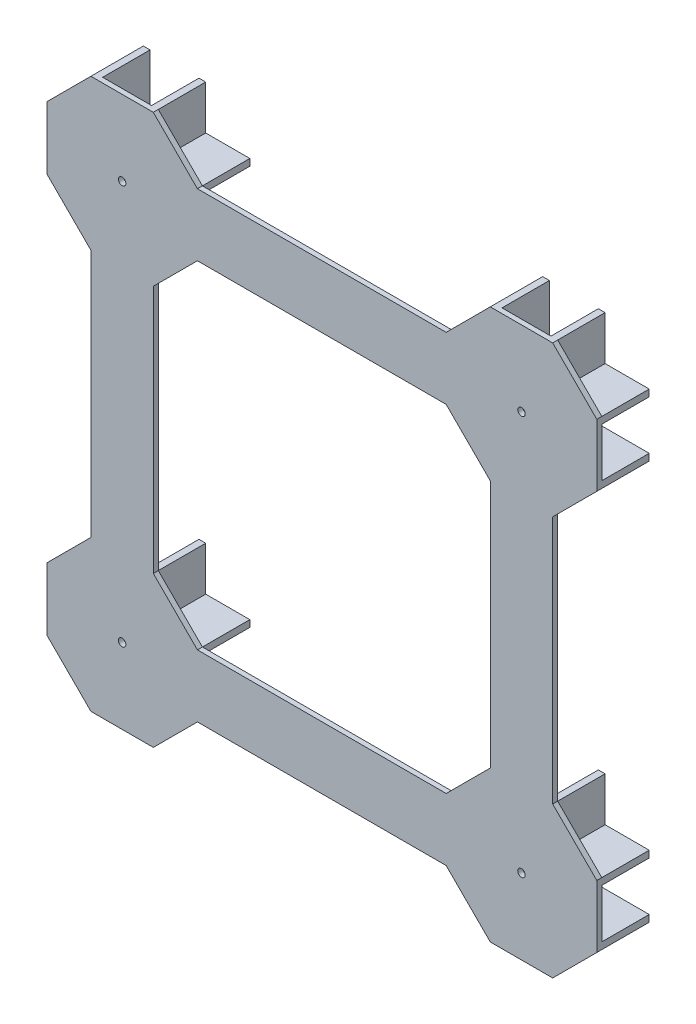
SolidWorks part; units mm, degrees
ref_plane "Front Plane" through (0, 0, 0) normal (0, 0, 1) x (1, 0, 0)
ref_plane "Top Plane" through (0, 0, 0) normal (0, 1, 0) x (1, 0, 0)
ref_plane "Right Plane" through (0, 0, 0) normal (1, 0, 0) x (0, 0, -1)
sketch "Sketch1" plane through (0, 0, 0) normal (0, 0, 1) x (1, 0, 0)
  line L0 (12.5, -110.1777) -> (-12.5, -110.1777)
  line L1 (-12.5, -110.1777) -> (-30.1777, -92.5)
  line L3 (-30.1777, -67.5) -> (-12.5, -49.8223)
  line L5 (12.5, -49.8223) -> (30.1777, -67.5)
  line L6 (30.1777, -67.5) -> (30.1777, -92.5)
  line L7 (30.1777, -92.5) -> (12.5, -110.1777)
  line L8 (9.5, 250) -> (9.5, -250) construction
  line L9 (-9.5, 250) -> (-9.5, -250) construction
  line L10 (9.5, -89.5) -> (170, -89.5) construction
  line L11 (-147.5, -110.1777) -> (-172.5, -110.1777)
  line L12 (-172.5, -110.1777) -> (-190.1777, -92.5)
  line L13 (-190.1777, -92.5) -> (-190.1777, -67.5)
  line L14 (-190.1777, -67.5) -> (-172.5, -49.8223)
  line L16 (-147.5, -49.8223) -> (-129.8223, -67.5)
  line L18 (-129.8223, -92.5) -> (-147.5, -110.1777)
  line L20 (-172.5, 49.8223) -> (-190.1777, 67.5)
  line L21 (-190.1777, 67.5) -> (-190.1777, 92.5)
  line L22 (-190.1777, 92.5) -> (-172.5, 110.1777)
  line L23 (-172.5, 110.1777) -> (-147.5, 110.1777)
  line L24 (-147.5, 110.1777) -> (-129.8223, 92.5)
  line L25 (-129.8223, 92.5) -> (-129.8223, 67.5) construction
  line L26 (-129.8223, 67.5) -> (-147.5, 49.8223)
  line L27 (12.5, 49.8223) -> (-12.5, 49.8223)
  line L28 (-12.5, 49.8223) -> (-30.1777, 67.5)
  line L30 (-30.1777, 92.5) -> (-12.5, 110.1777)
  line L31 (-12.5, 110.1777) -> (12.5, 110.1777)
  line L32 (12.5, 110.1777) -> (30.1777, 92.5)
  line L33 (30.1777, 92.5) -> (30.1777, 67.5)
  line L34 (30.1777, 67.5) -> (12.5, 49.8223)
  line L37 (-172.5, 49.8223) -> (-172.5, -49.8223)
  line L39 (-147.5, 49.8223) -> (-147.5, -49.8223)
  line L40 (-12.5, 49.8223) -> (12.5, 49.8223)
  line L41 (-12.5, 49.8223) -> (-12.5, -49.8223)
  line L43 (12.5, 49.8223) -> (12.5, -49.8223)
  line L44 (-30.1777, -67.5) -> (-129.8223, -67.5)
  line L46 (-30.1777, -92.5) -> (-129.8223, -92.5)
  line L48 (-129.8223, 67.5) -> (-30.1777, 67.5)
  line L49 (-129.8223, 67.5) -> (-129.8223, 92.5) construction
  line L50 (-129.8223, 92.5) -> (-30.1777, 92.5)
  line L54 (-129.8223, -67.5) -> (-129.8223, -92.5) [skipped]
  line L55 (-147.5, 49.8223) -> (-172.5, 49.8223) [skipped]
  dimension "D1" = 3
  dimension "D2" = 3
  dimension "D3" = 135
  dimension "D4" = 3
  dimension "D5" = 2
  dimension "D6" = 2
extrude "Boss-Extrude1" add sketch "Sketch1" along normal blind 2
sketch "Sketch2" plane through (0, 0, 0) normal (0, 0, -1) x (-1, 0, 0)
  line L0 (30.1777, -67.5) -> (12.5, -67.5)
  line L1 (12.5, -67.5) -> (12.5, -49.8223)
  line L2 (12.5, -49.8223) -> (9.8, -49.8223)
  line L4 (9.8, -49.8223) -> (9.8, -70.2)
  line L5 (9.8, -70.2) -> (30.1777, -70.2)
  line L7 (30.1777, -70.2) -> (30.1777, -67.5)
  line L8 (9.5, 250) -> (9.5, -250) construction
  line L9 (12.5, -92.5) -> (30.1777, -92.5)
  line L10 (30.1777, -92.5) -> (30.1777, -89.8)
  line L11 (30.1777, -89.8) -> (9.8, -89.8)
  line L12 (12.5, -110.1777) -> (12.5, -92.5)
  line L13 (9.8, -110.1777) -> (12.5, -110.1777)
  line L14 (9.8, -89.8) -> (9.8, -110.1777)
  line L15 (-12.5, -92.5) -> (-12.5, -110.1777)
  line L16 (-12.5, -110.1777) -> (-9.8, -110.1777)
  line L17 (-9.8, -110.1777) -> (-9.8, -89.8)
  line L18 (-30.1777, -92.5) -> (-12.5, -92.5)
  line L19 (-30.1777, -89.8) -> (-30.1777, -92.5)
  line L20 (-9.8, -89.8) -> (-30.1777, -89.8)
  line L21 (-12.5, -67.5) -> (-30.1777, -67.5)
  line L22 (-30.1777, -67.5) -> (-30.1777, -70.2)
  line L23 (-30.1777, -70.2) -> (-9.8, -70.2)
  line L24 (-12.5, -49.8223) -> (-12.5, -67.5)
  line L25 (-9.8, -49.8223) -> (-12.5, -49.8223)
  line L26 (-9.8, -70.2) -> (-9.8, -49.8223)
  line L27 (190.1777, -67.5) -> (172.5, -67.5)
  line L28 (172.5, -67.5) -> (172.5, -49.8223)
  line L29 (172.5, -49.8223) -> (169.8, -49.8223)
  line L30 (169.8, -49.8223) -> (169.8, -70.2)
  line L31 (169.8, -70.2) -> (190.1777, -70.2)
  line L32 (190.1777, -70.2) -> (190.1777, -67.5)
  line L33 (172.5, -92.5) -> (190.1777, -92.5)
  line L34 (190.1777, -92.5) -> (190.1777, -89.8)
  line L35 (190.1777, -89.8) -> (169.8, -89.8)
  line L36 (172.5, -110.1777) -> (172.5, -92.5)
  line L37 (169.8, -110.1777) -> (172.5, -110.1777)
  line L38 (169.8, -89.8) -> (169.8, -110.1777)
  line L39 (147.5, -92.5) -> (147.5, -110.1777)
  line L40 (147.5, -110.1777) -> (150.2, -110.1777)
  line L41 (150.2, -110.1777) -> (150.2, -89.8)
  line L42 (129.8223, -92.5) -> (147.5, -92.5)
  line L43 (129.8223, -89.8) -> (129.8223, -92.5)
  line L44 (150.2, -89.8) -> (129.8223, -89.8)
  line L45 (147.5, -67.5) -> (129.8223, -67.5)
  line L46 (129.8223, -67.5) -> (129.8223, -70.2)
  line L47 (129.8223, -70.2) -> (150.2, -70.2)
  line L48 (147.5, -49.8223) -> (147.5, -67.5)
  line L49 (150.2, -49.8223) -> (147.5, -49.8223)
  line L50 (150.2, -70.2) -> (150.2, -49.8223)
  line L51 (190.1777, 92.5) -> (172.5, 92.5)
  line L52 (172.5, 92.5) -> (172.5, 110.1777)
  line L53 (172.5, 110.1777) -> (169.8, 110.1777)
  line L54 (169.8, 110.1777) -> (169.8, 89.8)
  line L55 (169.8, 89.8) -> (190.1777, 89.8)
  line L56 (190.1777, 89.8) -> (190.1777, 92.5)
  line L57 (172.5, 67.5) -> (190.1777, 67.5)
  line L58 (190.1777, 67.5) -> (190.1777, 70.2)
  line L59 (190.1777, 70.2) -> (169.8, 70.2)
  line L60 (172.5, 49.8223) -> (172.5, 67.5)
  line L61 (169.8, 49.8223) -> (172.5, 49.8223)
  line L62 (169.8, 70.2) -> (169.8, 49.8223)
  line L63 (147.5, 67.5) -> (147.5, 49.8223)
  line L64 (147.5, 49.8223) -> (150.2, 49.8223)
  line L65 (150.2, 49.8223) -> (150.2, 70.2)
  line L66 (129.8223, 67.5) -> (147.5, 67.5)
  line L67 (129.8223, 70.2) -> (129.8223, 67.5)
  line L68 (150.2, 70.2) -> (129.8223, 70.2)
  line L69 (147.5, 92.5) -> (129.8223, 92.5)
  line L70 (129.8223, 92.5) -> (129.8223, 89.8)
  line L71 (129.8223, 89.8) -> (150.2, 89.8)
  line L72 (147.5, 110.1777) -> (147.5, 92.5)
  line L73 (150.2, 110.1777) -> (147.5, 110.1777)
  line L74 (150.2, 89.8) -> (150.2, 110.1777)
  line L75 (30.1777, 92.5) -> (12.5, 92.5)
  line L76 (12.5, 92.5) -> (12.5, 110.1777)
  line L77 (12.5, 110.1777) -> (9.8, 110.1777)
  line L78 (9.8, 110.1777) -> (9.8, 89.8)
  line L79 (9.8, 89.8) -> (30.1777, 89.8)
  line L80 (30.1777, 89.8) -> (30.1777, 92.5)
  line L81 (12.5, 67.5) -> (30.1777, 67.5)
  line L82 (30.1777, 67.5) -> (30.1777, 70.2)
  line L83 (30.1777, 70.2) -> (9.8, 70.2)
  line L84 (12.5, 49.8223) -> (12.5, 67.5)
  line L85 (9.8, 49.8223) -> (12.5, 49.8223)
  line L86 (9.8, 70.2) -> (9.8, 49.8223)
  line L87 (-12.5, 67.5) -> (-12.5, 49.8223)
  line L88 (-12.5, 49.8223) -> (-9.8, 49.8223)
  line L89 (-9.8, 49.8223) -> (-9.8, 70.2)
  line L90 (-30.1777, 67.5) -> (-12.5, 67.5)
  line L91 (-30.1777, 70.2) -> (-30.1777, 67.5)
  line L92 (-9.8, 70.2) -> (-30.1777, 70.2)
  line L93 (-12.5, 92.5) -> (-30.1777, 92.5)
  line L94 (-30.1777, 92.5) -> (-30.1777, 89.8)
  line L95 (-30.1777, 89.8) -> (-9.8, 89.8)
  line L96 (-12.5, 110.1777) -> (-12.5, 92.5)
  line L97 (-9.8, 110.1777) -> (-12.5, 110.1777)
  line L98 (-9.8, 89.8) -> (-9.8, 110.1777)
  circle A0 centre (0, -80) radius 30.1777 construction
  circle A1 centre (160, -80) radius 30.1777 construction
  circle A2 centre (160, 80) radius 30.1777 construction
  circle A3 centre (0, 80) radius 30.1777 construction
  point P38 (0, -80)
  point P61 (160, -80)
  point P88 (160, 80)
  point P115 (0, 80)
  dimension "D1" = 0.3
  dimension "D3" = 2
  dimension "D4" = 2
  dimension "D2" = 4
extrude "Boss-Extrude2" add sketch "Sketch2" along normal blind 19
sketch "Sketch6" plane through (0, 0, 2) normal (0, 0, 1) x (1, 0, 0)
  line L0 (-172.5, 49.8223) -> (-190.1777, 67.5) construction
  line L1 (-129.8223, 67.5) -> (-147.5, 49.8223) construction
  line L2 (-172.5, 110.1777) -> (-147.5, 110.1777) construction
  line L3 (-147.5, -49.8223) -> (-129.8223, -67.5) construction
  line L4 (-147.5, -110.1777) -> (-172.5, -110.1777) construction
  line L5 (-190.1777, -67.5) -> (-172.5, -49.8223) construction
  line L6 (12.5, -110.1777) -> (-12.5, -110.1777) construction
  line L7 (30.1777, -67.5) -> (30.1777, -92.5) construction
  line L8 (-30.1777, -67.5) -> (-12.5, -49.8223) construction
  line L9 (-30.1777, 92.5) -> (-12.5, 110.1777) construction
  line L10 (-12.5, 49.8223) -> (-30.1777, 67.5) construction
  line L11 (30.1777, 92.5) -> (30.1777, 67.5) construction
  circle A0 centre (-160, -80) radius 30.1777 construction
  circle A1 centre (-160, 80) radius 30.1777 construction
  circle A2 centre (0, 80) radius 30.1777 construction
  circle A3 centre (0, -80) radius 30.1777 construction
  circle A4 centre (-160, 80) radius 1.5
  circle A5 centre (0, 80) radius 1.5
  circle A6 centre (-160, -80) radius 1.5
  circle A7 centre (0, -80) radius 1.5
  dimension "D1" = 3
extrude "Cut-Extrude1" cut sketch "Sketch6" against normal through all
